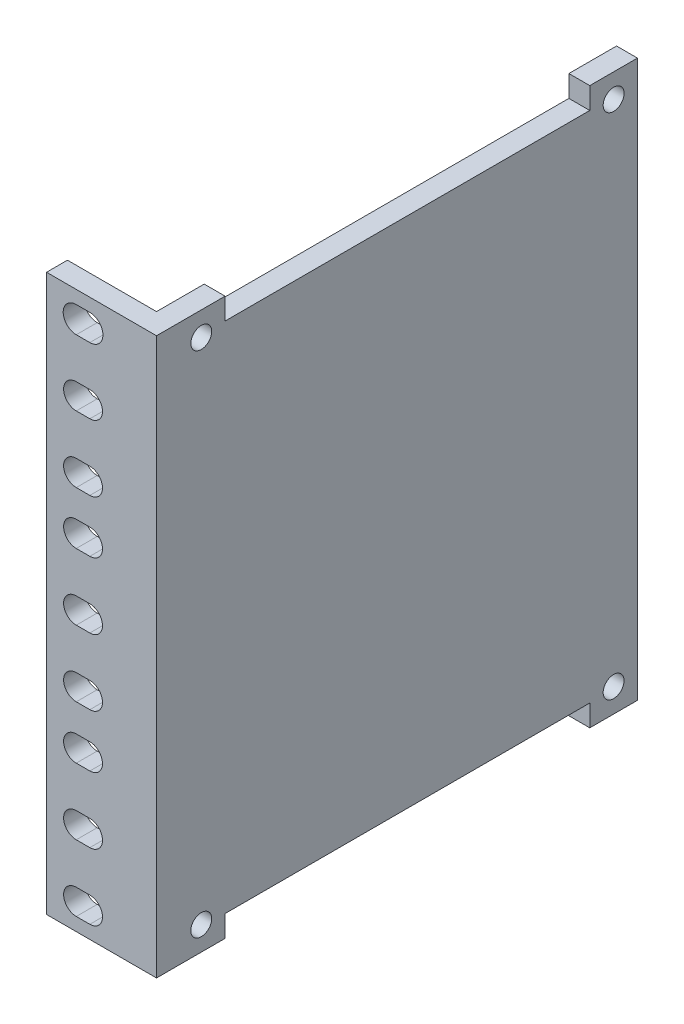
SolidWorks part; units mm, degrees
ref_plane "Front Plane" through (0, 0, 0) normal (0, 0, 1) x (1, 0, 0)
ref_plane "Top Plane" through (0, 0, 0) normal (0, 1, 0) x (1, 0, 0)
ref_plane "Right Plane" through (0, 0, 0) normal (1, 0, 0) x (0, 0, -1)
sketch "Sketch1" plane through (0, 0, 0) normal (0, 0, 1) x (1, 0, 0)
  line L0 (193.4516, 440.9203) -> (193.4516, 574.2703) construction
  line L1 (-47.8484, 574.2703) -> (434.7516, 574.2703) construction
  line L2 (-47.8484, 574.2703) -> (-47.8484, 440.9203) construction
  line L3 (-47.8484, 440.9203) -> (434.7516, 440.9203) construction
  line L4 (434.7516, 574.2703) -> (434.7516, 440.9203) construction
  line L5 (-47.8484, 507.5953) -> (434.7516, 507.5953) construction
  line L7 (-39.1171, 574.2703) -> (-39.1171, 440.9203) construction
  line L8 (354.6539, 507.5953) -> (233.6539, 507.5953) construction
  line L9 (426.0204, 574.2703) -> (426.0204, 440.9203) construction
  line L10 (-32.2171, 574.0953) -> (-32.2171, 529.8203) construction
  line L11 (-43.7671, 547.3078) -> (-34.4671, 547.3078) construction
  line L12 (-43.7671, 547.3078) -> (-43.7671, 556.6078) construction
  line L13 (-43.7671, 556.6078) -> (-34.4671, 556.6078) construction
  line L14 (-34.4671, 547.3078) -> (-34.4671, 556.6078) construction
  line L15 (-43.7671, 547.3078) -> (-34.4671, 556.6078) construction
  line L16 (-43.7671, 556.6078) -> (-34.4671, 547.3078) construction
  line L17 (-43.7671, 442.6203) -> (-34.4671, 442.6203) construction
  line L18 (-43.7671, 442.6203) -> (-43.7671, 451.9203) construction
  line L19 (-43.7671, 451.9203) -> (-34.4671, 451.9203) construction
  line L20 (-34.4671, 442.6203) -> (-34.4671, 451.9203) construction
  line L21 (-43.7671, 442.6203) -> (-34.4671, 451.9203) construction
  line L22 (-43.7671, 451.9203) -> (-34.4671, 442.6203) construction
  line L39 (-43.7671, 531.4328) -> (-34.4671, 531.4328) construction
  line L40 (-43.7671, 531.4328) -> (-43.7671, 540.7328) construction
  line L45 (-43.7671, 540.7328) -> (-34.4671, 540.7328) construction
  line L46 (-34.4671, 531.4328) -> (-34.4671, 540.7328) construction
  line L51 (-43.7671, 531.4328) -> (-34.4671, 540.7328) construction
  line L52 (-43.7671, 540.7328) -> (-34.4671, 531.4328) construction
  line L53 (-43.7671, 518.8203) -> (-34.4671, 518.8203) construction
  line L54 (-43.7671, 518.8203) -> (-43.7671, 528.1203) construction
  line L55 (-43.7671, 528.1203) -> (-34.4671, 528.1203) construction
  line L56 (-34.4671, 518.8203) -> (-34.4671, 528.1203) construction
  line L57 (-43.7671, 518.8203) -> (-34.4671, 528.1203) construction
  line L58 (-43.7671, 528.1203) -> (-34.4671, 518.8203) construction
  line L59 (-43.7671, 474.3703) -> (-34.4671, 474.3703) construction
  line L60 (-43.7671, 474.3703) -> (-43.7671, 483.6703) construction
  line L61 (-43.7671, 483.6703) -> (-34.4671, 483.6703) construction
  line L62 (-34.4671, 474.3703) -> (-34.4671, 483.6703) construction
  line L63 (-43.7671, 474.3703) -> (-34.4671, 483.6703) construction
  line L64 (-43.7671, 483.6703) -> (-34.4671, 474.3703) construction
  line L65 (-43.7671, 487.0703) -> (-34.4671, 487.0703) construction
  line L66 (-43.7671, 487.0703) -> (-43.7671, 496.3703) construction
  line L67 (-43.7671, 496.3703) -> (-34.4671, 496.3703) construction
  line L68 (-34.4671, 487.0703) -> (-34.4671, 496.3703) construction
  line L69 (-43.7671, 487.0703) -> (-34.4671, 496.3703) construction
  line L70 (-43.7671, 496.3703) -> (-34.4671, 487.0703) construction
  line L71 (-43.7671, 563.1828) -> (-34.4671, 563.1828) construction
  line L72 (-43.7671, 563.1828) -> (-43.7671, 572.4828) construction
  line L73 (-43.7671, 572.4828) -> (-34.4671, 572.4828) construction
  line L74 (-34.4671, 563.1828) -> (-34.4671, 572.4828) construction
  line L75 (-43.7671, 563.1828) -> (-34.4671, 572.4828) construction
  line L76 (-43.7671, 572.4828) -> (-34.4671, 563.1828) construction
  line L77 (-43.7671, 502.9453) -> (-34.4671, 502.9453) construction
  line L78 (-43.7671, 502.9453) -> (-43.7671, 512.2453) construction
  line L79 (-43.7671, 512.2453) -> (-34.4671, 512.2453) construction
  line L80 (-34.4671, 502.9453) -> (-34.4671, 512.2453) construction
  line L81 (-43.7671, 502.9453) -> (-34.4671, 512.2453) construction
  line L82 (-43.7671, 512.2453) -> (-34.4671, 502.9453) construction
  line L83 (-43.7671, 458.4953) -> (-34.4671, 458.4953) construction
  line L84 (-43.7671, 458.4953) -> (-43.7671, 467.7953) construction
  line L85 (-43.7671, 467.7953) -> (-34.4671, 467.7953) construction
  line L86 (-34.4671, 458.4953) -> (-34.4671, 467.7953) construction
  line L87 (-43.7671, 458.4953) -> (-34.4671, 467.7953) construction
  line L88 (-43.7671, 467.7953) -> (-34.4671, 458.4953) construction
  line L89 (-47.8484, 529.8203) -> (434.7516, 529.8203) construction
  line L90 (434.7516, 485.3703) -> (-47.8484, 485.3703) construction
  line L91 (-32.2171, 529.8203) -> (-32.2171, 485.3703) construction
  line L92 (-32.2171, 485.3703) -> (-32.2171, 440.9203) construction
  line L93 (-32.2171, 551.9578) -> (426.0204, 551.9578) construction
  line L94 (-32.2171, 463.1453) -> (426.0204, 463.1453) construction
  line L95 (-34.4671, 563.1828) -> (-34.4671, 540.7328) construction
  line L96 (-32.2171, 551.9578) -> (-34.4671, 551.9578) construction
  line L97 (-34.4671, 518.8203) -> (-34.4671, 496.3703) construction
  line L98 (-34.4671, 474.3703) -> (-34.4671, 451.9203) construction
  line L99 (-34.4671, 463.1453) -> (-32.2171, 463.1453) construction
  line L100 (419.1204, 574.2703) -> (419.1204, 440.9203) construction
  line L101 (-40.7421, 567.8328) -> (-37.4921, 567.8328) construction
  line L102 (-48.3484, 574.2703) -> (-34.7171, 574.2703) construction
  line L103 (-47.8484, 572.2703) -> (-47.8484, 442.9203)
  line L104 (-48.3484, 440.9203) -> (-32.2171, 440.9203) construction
  line L105 (-32.2171, 574.0953) -> (-32.2171, 440.9203)
  line L106 (-40.7421, 570.9578) -> (-37.4921, 570.9578)
  line L107 (-40.7421, 564.7078) -> (-37.4921, 564.7078)
  line L108 (-40.7421, 551.9578) -> (-37.4921, 551.9578) construction
  line L111 (-40.7421, 554.9828) -> (-37.4921, 554.9828)
  line L114 (-40.7421, 548.9328) -> (-37.4921, 548.9328)
  line L117 (-37.4921, 567.8328) -> (-37.4921, 570.2125) construction
  line L120 (-40.7421, 567.8328) -> (-40.7421, 570.3) construction
  line L123 (-40.7421, 536.0828) -> (-37.4921, 536.0828) construction
  line L126 (-40.7421, 539.1078) -> (-37.4921, 539.1078)
  line L129 (-40.7421, 533.0578) -> (-37.4921, 533.0578)
  line L130 (-40.7421, 507.5953) -> (-37.4921, 507.5953) construction
  line L131 (-40.7421, 510.6203) -> (-37.4921, 510.6203)
  line L132 (-40.7421, 504.5703) -> (-37.4921, 504.5703)
  line L133 (-40.7421, 491.7203) -> (-37.4921, 491.7203) construction
  line L134 (-40.7421, 494.7453) -> (-37.4921, 494.7453)
  line L135 (-40.7421, 488.6953) -> (-37.4921, 488.6953)
  line L136 (-40.7421, 463.1453) -> (-37.4921, 463.1453) construction
  line L137 (-40.7421, 466.1703) -> (-37.4921, 466.1703)
  line L138 (-40.7421, 460.1203) -> (-37.4921, 460.1203)
  line L139 (-40.7421, 479.0203) -> (-37.4921, 479.0203) construction
  line L140 (-40.7421, 482.0453) -> (-37.4921, 482.0453)
  line L141 (-40.7421, 475.9953) -> (-37.4921, 475.9953)
  line L142 (-40.7421, 523.4703) -> (-37.4921, 523.4703) construction
  line L143 (-40.7421, 526.4953) -> (-37.4921, 526.4953)
  line L144 (-40.7421, 520.4453) -> (-37.4921, 520.4453)
  line L145 (-40.7421, 447.2703) -> (-37.4921, 447.2703) construction
  line L146 (-40.7421, 450.2953) -> (-37.4921, 450.2953)
  line L147 (-40.7421, 444.2453) -> (-37.4921, 444.2453)
  line L148 (-21.5484, 574.0953) -> (21.4516, 574.0953) construction
  line L149 (408.4516, 456.5953) -> (408.4516, 441.0953) construction
  line L150 (-26.5484, 446.0953) -> (-26.5484, 441.0953) construction
  line L151 (-26.5484, 569.0953) -> (-26.5484, 574.0953) construction
  line L153 (-32.2171, 574.0953) -> (-32.2171, 440.9203)
  line L155 (-30.2171, 574.0953) -> (-30.2171, 440.9203)
  line L156 (-26.5484, 569.0953) -> (-26.5484, 574.0953) construction
  line L157 (-21.5484, 574.0953) -> (-21.5484, 558.5953) construction
  line L159 (-30.2171, 574.0953) -> (-30.2171, 440.9203)
  line L161 (-26.5484, 574.0953) -> (-26.5484, 440.9203)
  line L162 (-21.5484, 574.0953) -> (-21.5484, 558.5953) construction
  line L165 (-21.5484, 574.0953) -> (21.4516, 574.0953)
  line L166 (-47.8484, 572.2703) -> (-47.8484, 574.0953)
  line L167 (-21.5484, 574.0953) -> (-47.8484, 574.0953) construction
  line L169 (-26.5484, 574.0953) -> (-26.5484, 440.9203)
  line L171 (-21.5484, 574.0953) -> (-21.5484, 440.9203)
  line L172 (-21.5484, 574.0953) -> (-47.8484, 574.0953)
  line L173 (-21.5484, 441.0953) -> (-47.8484, 441.0953) construction
  line L174 (-26.5484, 441.0953) -> (-21.5484, 441.0953) construction
  line L175 (-26.5484, 441.0953) -> (-21.5484, 441.0953) construction
  line L176 (-47.8484, 442.9203) -> (-47.8484, 441.0953)
  line L177 (-21.5484, 441.0953) -> (21.4516, 441.0953) construction
  line L178 (-47.8484, 441.0953) -> (-21.5484, 441.0953)
  line L179 (434.7516, 442.9203) -> (434.7516, 441.0953)
  line L180 (434.7516, 572.2703) -> (434.7516, 574.0953)
  line L181 (434.7516, 572.2703) -> (434.7516, 442.9203)
  line L182 (427.6454, 463.1453) -> (424.3954, 463.1453) construction
  line L183 (427.6454, 466.1703) -> (424.3954, 466.1703)
  line L184 (427.6454, 460.1203) -> (424.3954, 460.1203)
  line L185 (427.6454, 447.2703) -> (424.3954, 447.2703) construction
  line L186 (427.6454, 450.2953) -> (424.3954, 450.2953)
  line L187 (427.6454, 444.2453) -> (424.3954, 444.2453)
  line L188 (427.6454, 479.0203) -> (424.3954, 479.0203) construction
  line L189 (427.6454, 482.0453) -> (424.3954, 482.0453)
  line L190 (427.6454, 475.9953) -> (424.3954, 475.9953)
  line L191 (427.6454, 491.7203) -> (424.3954, 491.7203) construction
  line L192 (427.6454, 494.7453) -> (424.3954, 494.7453)
  line L193 (427.6454, 488.6953) -> (424.3954, 488.6953)
  line L194 (427.6454, 507.5953) -> (424.3954, 507.5953) construction
  line L195 (427.6454, 510.6203) -> (424.3954, 510.6203)
  line L196 (427.6454, 504.5703) -> (424.3954, 504.5703)
  line L197 (427.6454, 523.4703) -> (424.3954, 523.4703) construction
  line L198 (427.6454, 526.4953) -> (424.3954, 526.4953)
  line L199 (427.6454, 520.4453) -> (424.3954, 520.4453)
  line L200 (427.6454, 536.0828) -> (424.3954, 536.0828) construction
  line L201 (427.6454, 539.1078) -> (424.3954, 539.1078)
  line L202 (427.6454, 533.0578) -> (424.3954, 533.0578)
  line L203 (427.6454, 551.9578) -> (424.3954, 551.9578) construction
  line L204 (427.6454, 554.9828) -> (424.3954, 554.9828)
  line L205 (427.6454, 548.9328) -> (424.3954, 548.9328)
  line L206 (427.6454, 567.8328) -> (424.3954, 567.8328) construction
  line L207 (427.6454, 570.9578) -> (424.3954, 570.9578)
  line L208 (427.6454, 564.7078) -> (424.3954, 564.7078)
  line L209 (408.4516, 574.0953) -> (408.4516, 558.5953) construction
  line L210 (408.4516, 574.0953) -> (408.4516, 558.5953) construction
  line L211 (434.7516, 574.0953) -> (408.4516, 574.0953)
  line L212 (434.7516, 441.0953) -> (408.4516, 441.0953)
  line L213 (408.4516, 441.0953) -> (408.4516, 574.0953)
  line L214 (190.9516, 547.6801) -> (190.9516, 668.6801) construction
  arc A0 (-40.7421, 570.9578) -> (-40.7421, 564.7078) centre (-40.7421, 567.8328) ccw
  arc A1 (-37.4921, 564.7078) -> (-37.4921, 570.9578) centre (-37.4921, 567.8328) ccw
  arc A16 (-40.7421, 554.9828) -> (-40.7421, 548.9328) centre (-40.7421, 551.9578) ccw
  arc A17 (-37.4921, 548.9328) -> (-37.4921, 554.9828) centre (-37.4921, 551.9578) ccw
  arc A18 (-40.7421, 539.1078) -> (-40.7421, 533.0578) centre (-40.7421, 536.0828) ccw
  arc A19 (-37.4921, 533.0578) -> (-37.4921, 539.1078) centre (-37.4921, 536.0828) ccw
  arc A20 (-40.7421, 510.6203) -> (-40.7421, 504.5703) centre (-40.7421, 507.5953) ccw
  arc A21 (-37.4921, 504.5703) -> (-37.4921, 510.6203) centre (-37.4921, 507.5953) ccw
  arc A22 (-40.7421, 494.7453) -> (-40.7421, 488.6953) centre (-40.7421, 491.7203) ccw
  arc A23 (-37.4921, 488.6953) -> (-37.4921, 494.7453) centre (-37.4921, 491.7203) ccw
  arc A24 (-40.7421, 466.1703) -> (-40.7421, 460.1203) centre (-40.7421, 463.1453) ccw
  arc A25 (-37.4921, 460.1203) -> (-37.4921, 466.1703) centre (-37.4921, 463.1453) ccw
  arc A26 (-40.7421, 482.0453) -> (-40.7421, 475.9953) centre (-40.7421, 479.0203) ccw
  arc A27 (-37.4921, 475.9953) -> (-37.4921, 482.0453) centre (-37.4921, 479.0203) ccw
  arc A28 (-40.7421, 526.4953) -> (-40.7421, 520.4453) centre (-40.7421, 523.4703) ccw
  arc A29 (-37.4921, 520.4453) -> (-37.4921, 526.4953) centre (-37.4921, 523.4703) ccw
  arc A30 (-40.7421, 450.2953) -> (-40.7421, 444.2453) centre (-40.7421, 447.2703) ccw
  arc A31 (-37.4921, 444.2453) -> (-37.4921, 450.2953) centre (-37.4921, 447.2703) ccw
  arc A32 (427.6454, 466.1703) -> (427.6454, 460.1203) centre (427.6454, 463.1453) cw
  arc A33 (424.3954, 460.1203) -> (424.3954, 466.1703) centre (424.3954, 463.1453) cw
  arc A34 (427.6454, 450.2953) -> (427.6454, 444.2453) centre (427.6454, 447.2703) cw
  arc A35 (424.3954, 444.2453) -> (424.3954, 450.2953) centre (424.3954, 447.2703) cw
  arc A36 (427.6454, 482.0453) -> (427.6454, 475.9953) centre (427.6454, 479.0203) cw
  arc A37 (424.3954, 475.9953) -> (424.3954, 482.0453) centre (424.3954, 479.0203) cw
  arc A38 (427.6454, 494.7453) -> (427.6454, 488.6953) centre (427.6454, 491.7203) cw
  arc A39 (424.3954, 488.6953) -> (424.3954, 494.7453) centre (424.3954, 491.7203) cw
  arc A40 (427.6454, 510.6203) -> (427.6454, 504.5703) centre (427.6454, 507.5953) cw
  arc A41 (424.3954, 504.5703) -> (424.3954, 510.6203) centre (424.3954, 507.5953) cw
  arc A42 (427.6454, 526.4953) -> (427.6454, 520.4453) centre (427.6454, 523.4703) cw
  arc A43 (424.3954, 520.4453) -> (424.3954, 526.4953) centre (424.3954, 523.4703) cw
  arc A44 (427.6454, 539.1078) -> (427.6454, 533.0578) centre (427.6454, 536.0828) cw
  arc A45 (424.3954, 533.0578) -> (424.3954, 539.1078) centre (424.3954, 536.0828) cw
  arc A46 (427.6454, 554.9828) -> (427.6454, 548.9328) centre (427.6454, 551.9578) cw
  arc A47 (424.3954, 548.9328) -> (424.3954, 554.9828) centre (424.3954, 551.9578) cw
  arc A48 (427.6454, 570.9578) -> (427.6454, 564.7078) centre (427.6454, 567.8328) cw
  arc A49 (424.3954, 564.7078) -> (424.3954, 570.9578) centre (424.3954, 567.8328) cw
  point P16 (-39.1171, 551.9578)
  point P21 (-39.1171, 447.2703)
  point P28 (-39.1171, 536.0828)
  point P33 (-39.1171, 523.4703)
  point P38 (-39.1171, 479.0203)
  point P43 (-39.1171, 491.7203)
  point P49 (-39.1171, 567.8328)
  point P54 (-39.1171, 507.5953)
  point P66 (-39.1171, 463.1453)
  point P71 (-34.4671, 507.5953)
  point P82 (-39.1171, 567.8328)
  point P92 (-39.1171, 551.9578)
  point P100 (-39.1171, 536.0828)
  point P107 (-39.1171, 507.5953)
  point P114 (-39.1171, 491.7203)
  point P121 (-39.1171, 463.1453)
  point P128 (-39.1171, 479.0203)
  point P135 (-39.1171, 523.4703)
  point P142 (-39.1171, 447.2703)
  point P152 (-34.4671, 551.9578)
  point P154 (-34.4671, 536.0828)
  point P159 (-34.4671, 523.4703)
  point P162 (-34.4671, 507.5953)
  point P165 (-34.4671, 491.7203)
  point P168 (-34.4671, 479.0203)
  point P173 (-34.4671, 463.1453)
  point P179 (-34.4671, 447.2703)
  point P182 (426.0204, 463.1453)
  point P191 (426.0204, 447.2703)
  point P198 (426.0204, 479.0203)
  point P205 (426.0204, 491.7203)
  point P212 (426.0204, 507.5953)
  point P219 (426.0204, 523.4703)
  point P226 (426.0204, 536.0828)
  point P233 (426.0204, 551.9578)
  point P240 (426.0204, 567.8328)
  dimension "D24" = 2.5
  dimension "D1" = 482.6
  dimension "D2" = 133.35
  dimension "D3" = 232.5687
  dimension "D4" = 465.1375
  dimension "D5" = 9.3
  dimension "D6" = 2.25
  dimension "D7" = 9.3
  dimension "D8" = 31.75
  dimension "D9" = 31.75
  dimension "D10" = 9.3
  dimension "D11" = 9.3
  dimension "D12" = 9.3
  dimension "D13" = 9.3
  dimension "D14" = 31.75
  dimension "D15" = 44.45
  dimension "D16" = 6.9
  dimension "D17" = 451.3375
  dimension "D18" = 9.3
  dimension "D19" = 9.3
  dimension "D20" = 9.3
  dimension "D21" = 88.9
  dimension "D22" = 6.25
  dimension "D23" = 9.5
  dimension "D25" = 5.6688
  dimension "D26" = 10.6688
  dimension "D27" = 6.9
  dimension "D28" = 2
extrude "Boss-Extrude1" add sketch "Sketch1" along normal blind 5
sketch "Sketch2" plane through (-21.5484, 0, 0) normal (-1, 0, 0) x (0, 0, 1)
  line L0 (0, 558.5953) -> (0, 456.5953)
  line L16 (-11.4, 441.0953) -> (0, 441.0953)
  line L17 (-11.4, 446.2453) -> (-11.4, 441.0953)
  line L18 (-98.6, 446.2453) -> (-11.4, 446.2453)
  line L19 (-98.6, 441.0953) -> (-98.6, 446.2453)
  line L20 (-110, 441.0953) -> (-98.6, 441.0953)
  line L21 (-110, 574.0953) -> (-110, 441.0953)
  line L22 (-98.6, 574.0953) -> (-110, 574.0953)
  line L23 (-98.6, 568.9453) -> (-98.6, 574.0953)
  line L24 (-11.4, 568.9453) -> (-98.6, 568.9453)
  line L25 (-11.4, 574.0953) -> (-11.4, 568.9453)
  line L26 (0, 574.0953) -> (-11.4, 574.0953)
  line L27 (0, 558.5953) -> (0, 574.0953)
  line L28 (-100, 558.5953) -> (0, 558.5953)
  line L29 (-100, 456.5953) -> (-100, 558.5953)
  line L30 (0, 456.5953) -> (-100, 456.5953)
  line L31 (0, 441.0953) -> (0, 456.5953)
  line L32 (-11.4, 441.0953) -> (0, 441.0953)
  line L33 (-11.4, 446.2453) -> (-11.4, 441.0953)
  line L34 (-98.6, 446.2453) -> (-11.4, 446.2453)
  line L35 (-98.6, 441.0953) -> (-98.6, 446.2453)
  line L36 (-110, 441.0953) -> (-98.6, 441.0953)
  line L37 (-110, 574.0953) -> (-110, 441.0953)
  line L38 (-98.6, 574.0953) -> (-110, 574.0953)
  line L39 (-98.6, 568.9453) -> (-98.6, 574.0953)
  line L40 (-11.4, 568.9453) -> (-98.6, 568.9453)
  line L41 (-11.4, 574.0953) -> (-11.4, 568.9453)
  line L42 (0, 574.0953) -> (-11.4, 574.0953)
  line L43 (0, 558.5953) -> (0, 574.0953)
  line L44 (-100, 558.5953) -> (0, 558.5953) construction
  line L45 (-100, 456.5953) -> (-100, 558.5953) construction
  line L46 (0, 456.5953) -> (-100, 456.5953) construction
  line L47 (0, 441.0953) -> (0, 456.5953)
  circle A0 centre (-5.7, 568.3953) radius 2.5 construction
  circle A1 centre (-5.7, 568.3953) radius 2.5
  circle A2 centre (-104.3, 568.3953) radius 2.5 construction
  circle A3 centre (-104.3, 568.3953) radius 2.5
  circle A4 centre (-104.3, 446.7953) radius 2.5 construction
  circle A5 centre (-104.3, 446.7953) radius 2.5
  circle A6 centre (-5.7, 446.7953) radius 2.5 construction
  circle A7 centre (-5.7, 446.7953) radius 2.5
  dimension "D1" = 0
extrude "Boss-Extrude2" add sketch "Sketch2" along normal up to surface (5 mm away) separate body
sketch "Sketch4" plane through (0, 574.0953, 0) normal (0, 1, 0) x (1, 0, 0)
  line L1 (-26.5484, 0) -> (-26.5484, 11.4) construction
  line L2 (-26.5484, 0) -> (-29.5484, 0)
  line L3 (-26.5484, 0) -> (-26.5484, 10)
  line L4 (-26.5484, 10) -> (-29.5484, 0)
  dimension "D1" = 3
  dimension "D2" = 10
extrude "Boss-Extrude3" add sketch "Sketch4" against normal offset from surface (103 mm away) 15 from offset 15 up to face at (-24.0484, 441.0953, -5.7) offset against normal yes
sketch "Sketch5" plane through (0, 0, -110) normal (0, 0, -1) x (-1, 0, 0)
  line L1 (-2.909, 580.2473) -> (56.4554, 580.2473)
  line L2 (-2.909, 580.2473) -> (-2.909, 431.1563)
  line L3 (-2.909, 431.1563) -> (56.4554, 431.1563)
  line L4 (56.4554, 580.2473) -> (56.4554, 431.1563)
extrude "Cut-Extrude1" [suppressed] cut sketch "Sketch5" against normal offset from surface (93.6 mm away) 5
